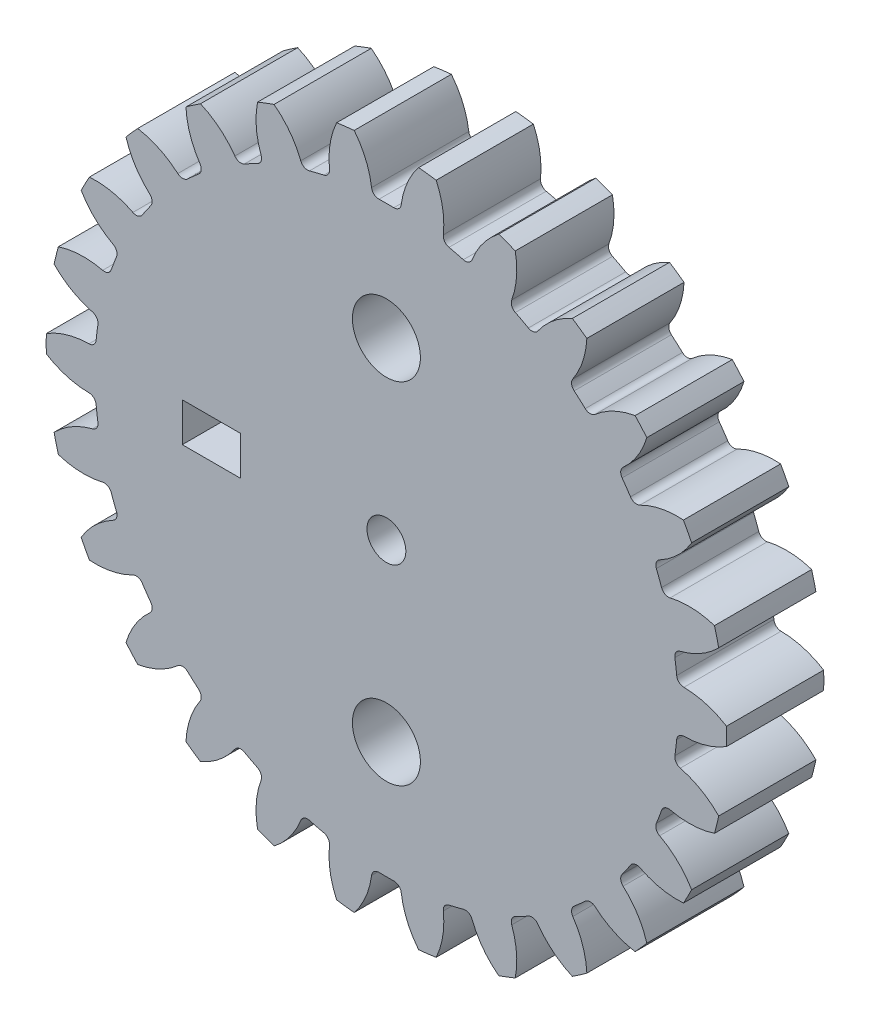
SolidWorks part; units mm, degrees
ref_plane "Front" through (0, 0, 0) normal (0, 0, 1) x (1, 0, 0)
ref_plane "Top" through (0, 0, 0) normal (0, 1, 0) x (1, 0, 0)
ref_plane "Right" through (0, 0, 0) normal (1, 0, 0) x (0, 0, -1)
sketch "Sketch1" plane through (0, 0, 0) normal (0, 0, 1) x (1, 0, 0)
  circle A0 centre (0, 0) radius 15
  circle A1 centre (0, 0) radius 17.5
  circle A2 centre (0, 0) radius 16.25
  dimension "D1" = 35
  dimension "D2" = 30
  dimension "D3" = 32.5
extrude "Boss-Extrude1" add sketch "Sketch1" along normal mid plane 5 contours A1
sketch "Sketch3" plane through (0, 0, 0) normal (0, 0, 1) x (1, 0, 0)
  line L0 (0, 0) -> (0, 17.5) construction
  line L1 (0, 0) -> (-0.7315, 14.9822) construction
  line L2 (-0.9812, 16.2204) -> (0.9812, 16.2204) construction
  line L3 (-1.4257, 17.4418) -> (0, 13.5247) construction
  line L4 (0, 0) -> (2.1094, 17.3724) construction
  line L5 (0.9812, 16.2204) -> (2.9291, 15.9838) construction
  arc A0 (-0.7315, 14.9822) -> (0.7315, 14.9822) centre (0, 0) cw
  arc A4 (1.6577, 17.4213) -> (-1.6577, 17.4213) centre (0, 0) ccw
  circle A5 centre (0, 0) radius 17.5 construction
  arc A7 (-1.6577, 17.4213) -> (-0.7315, 14.9822) centre (-4.9488, 14.7762) cw
  arc A10 (1.6577, 17.4213) -> (0.7315, 14.9822) centre (4.9488, 14.7762) ccw
  circle A11 centre (0, 0) radius 15 construction
  circle A12 centre (0, 0) radius 16.25 construction
  dimension "D1" = 20
  dimension "D2" = 6.923
extrude "Cut-Extrude1" cut sketch "Sketch3" against normal through all both and the other way through all
fillet "Fillet2" radius 0.375 2 edges at (0.7315, 14.9822, 0) (-0.7315, 14.9822, 0)
pattern_circular "CirPattern1" count 26 over 360 about axis through (0, 0, 0) along (0, 0, 1) of "Cut-Extrude1", "Fillet2"
sketch "Sketch4" plane through (0, 0, 0) normal (0, 0, 1) x (1, 0, 0)
  circle A0 centre (0, 0) radius 1
  dimension "D1" = 2
extrude "String_Hole" cut sketch "Sketch4" against normal through all both and the other way through all
sketch "Sketch5" plane through (0, 0, 0) normal (0, 0, 1) x (1, 0, 0)
  line L0 (0, -9) -> (0, 9) construction
  circle A0 centre (0, 9) radius 1.75
  circle A1 centre (0, -9) radius 1.75
  dimension "D2" = 3.5
  dimension "D1" = 18
extrude "To_Knuckle_Mount" cut sketch "Sketch5" against normal through all both and the other way through all
sketch "Sketch7" plane through (0, 0, 2.5) normal (0, 0, 1) x (1, 0, 0)
  line L1 (-10.5, -1) -> (-7.5, -1)
  line L2 (-10.5, -1) -> (-10.5, 1)
  line L3 (-10.5, 1) -> (-7.5, 1)
  line L4 (-7.5, -1) -> (-7.5, 1)
  line L5 (-10.5, -1) -> (-7.5, 1) construction
  line L6 (-10.5, 1) -> (-7.5, -1) construction
  line L7 (0, 0) -> (-17.5, 0) construction
  arc A1 (-17.4941, 0.4543) -> (-17.4941, -0.4543) centre (0, 0) ccw construction
  point P0 (-9, 0)
  dimension "D1" = 3
  dimension "D2" = 2
  dimension "D3" = 9
extrude "For_Alignment" cut sketch "Sketch7" against normal blind 2
equation "\"od\"= 35'outside diameter"
equation "\"n\"= 26'number of teeth"
equation "\"m\"= \"od\" / ( \"n\" + 2 )'module"
equation "\"p\"= \"m\" * pi'pitch"
equation "\"d\"= \"m\" * \"n\"'primitive diameter"
equation "\"da\"= \"d\" + 2 * \"m\"'head diamater"
equation "\"df\"= \"d\" - 2 * \"m\"'foot diameter"
equation "\"D1@Sketch1\"=\"od\""
equation "\"D2@Sketch1\"=\"df\""
equation "\"D3@Sketch1\"=\"d\""
equation "\"D2@Sketch3\"=180/\"n\""
equation "\"D1@Fillet2\"=.3*\"m\""
equation "\"D1@CirPattern1\"=\"n\""
